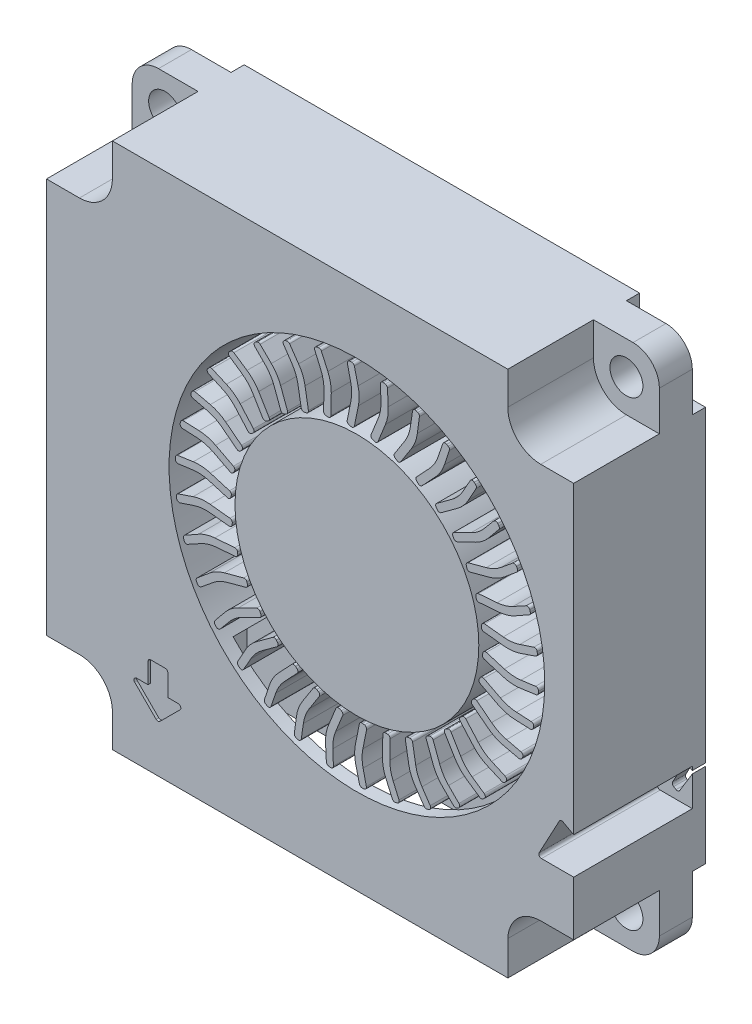
SolidWorks part; units mm, degrees
material "ABS"
ref_plane "Спереди" through (0, 0, 0) normal (0, 0, 1) x (1, 0, 0)
ref_plane "Сверху" through (0, 0, 0) normal (0, 1, 0) x (1, 0, 0)
ref_plane "Справа" through (0, 0, 0) normal (1, 0, 0) x (0, 0, -1)
sketch "Эскиз1" plane through (0, 0, 0) normal (0, 0, 1) x (1, 0, 0)
  line L1 (2, 0) -> (38, 0)
  line L2 (0, 2) -> (0, 38)
  line L3 (2, 40) -> (38, 40)
  line L4 (40, 2) -> (40, 38)
  arc A0 (0, 2) -> (2, 0) centre (2, 2) ccw
  arc A1 (40, 2) -> (38, 0) centre (38, 2) cw
  arc A2 (40, 38) -> (38, 40) centre (38, 38) ccw
  arc A3 (0, 38) -> (2, 40) centre (2, 38) cw
  circle A4 centre (2.5, 37.5) radius 1.25
  circle A5 centre (37.5, 37.5) radius 1.25
  circle A6 centre (37.5, 2.5) radius 1.25
  circle A7 centre (2.5, 2.5) radius 1.25
  point P7 (0, 0)
  point P10 (40, 0)
  point P13 (40, 40)
  point P16 (0, 40)
  dimension "D3" = 2
  dimension "D4" = 2
  dimension "D6" = 2.5
  dimension "D1" = 40
  dimension "D2" = 40
  dimension "D7" = 2.5
  dimension "D5" = 2
extrude "Бобышка-Вытянуть1" add sketch "Эскиз1" along normal blind 10
sketch "Эскиз2" plane through (0, 0, 10) normal (0, 0, 1) x (1, 0, 0)
  line L0 (5, 37.5) -> (5, 40)
  line L1 (5, 40) -> (-1.1472, 40)
  line L2 (-1.1472, 40) -> (-1.1472, 35)
  line L3 (-1.1472, 35) -> (2.5, 35)
  line L4 (37.5, 35) -> (44.7203, 35)
  line L5 (44.7203, 35) -> (44.7203, 44.1762)
  line L6 (44.7203, 44.1762) -> (35, 44.1762)
  line L7 (35, 44.1762) -> (35, 37.5)
  line L8 (37.5, 5.0016) -> (44.7203, 5.0016)
  line L9 (44.7203, 5.0016) -> (44.7203, -1.7129)
  line L10 (44.7203, -1.7129) -> (35.0111, -1.7129)
  line L11 (35.0111, -1.7129) -> (35, 2.5894)
  line L12 (5, 2.5) -> (5, -3.0182)
  line L13 (5, -3.0182) -> (-5.3068, -3.0182)
  line L14 (-5.3068, -3.0182) -> (-5.3068, 5)
  line L15 (-5.3068, 5) -> (2.5, 5)
  arc A0 (2.5, 35) -> (5, 37.5) centre (2.5, 37.5) ccw
  arc A1 (35, 37.5) -> (37.5, 35) centre (37.5, 37.5) ccw
  arc A2 (37.5, 5.0016) -> (35, 2.5894) centre (37.5, 2.5) ccw
  arc A3 (5, 2.5) -> (2.5, 5) centre (2.5, 2.5) ccw
extrude "Вырез-Вытянуть1" cut sketch "Эскиз2" against normal blind 6.5
sketch "Эскиз4" plane through (0, 0, 10) normal (0, 0, 1) x (1, 0, 0)
  line L0 (2, 0) -> (5, 0) construction
  line L1 (5, 0) -> (5, 2.5) construction
  line L2 (2.5, 5) -> (0, 5) construction
  line L3 (0, 5) -> (0, 2) construction
  line L4 (35.0067, 0) -> (38, 0) construction
  line L5 (40, 2) -> (40, 5.0016) construction
  line L6 (40, 5.0016) -> (37.5, 5.0016) construction
  line L7 (35, 2.5894) -> (35.0067, 0) construction
  line L8 (40, 35) -> (40, 38) construction
  line L9 (38, 40) -> (35, 40) construction
  line L10 (35, 40) -> (35, 37.5) construction
  line L11 (37.5, 35) -> (40, 35) construction
  line L12 (0, 38) -> (0, 35) construction
  line L13 (0, 35) -> (2.5, 35) construction
  line L14 (5, 37.5) -> (5, 40) construction
  line L15 (5, 40) -> (2, 40) construction
  line L16 (2, 0) -> (5, 0)
  line L17 (5, 0) -> (5, 2.5)
  line L18 (2.5, 5) -> (0, 5)
  line L19 (0, 5) -> (0, 2)
  line L20 (35.0067, 0) -> (38, 0)
  line L21 (40, 2) -> (40, 5.0016)
  line L22 (40, 5.0016) -> (37.5, 5.0016)
  line L23 (35, 2.5894) -> (35.0067, 0)
  line L24 (40, 35) -> (40, 38)
  line L25 (38, 40) -> (35, 40)
  line L26 (35, 40) -> (35, 37.5)
  line L27 (37.5, 35) -> (40, 35)
  line L28 (0, 38) -> (0, 35)
  line L29 (0, 35) -> (2.5, 35)
  line L30 (5, 37.5) -> (5, 40)
  line L31 (5, 40) -> (2, 40)
  arc A0 (5, 2.5) -> (2.5, 5) centre (2.5, 2.5) ccw construction
  arc A1 (0, 2) -> (2, 0) centre (2, 2) ccw construction
  arc A2 (38, 0) -> (40, 2) centre (38, 2) ccw construction
  arc A3 (37.5, 5.0016) -> (35, 2.5894) centre (37.5, 2.5) ccw construction
  arc A4 (40, 38) -> (38, 40) centre (38, 38) ccw construction
  arc A5 (35, 37.5) -> (37.5, 35) centre (37.5, 37.5) ccw construction
  arc A6 (2, 40) -> (0, 38) centre (2, 38) ccw construction
  arc A7 (2.5, 35) -> (5, 37.5) centre (2.5, 37.5) ccw construction
  arc A8 (5, 2.5) -> (2.5, 5) centre (2.5, 2.5) ccw
  arc A9 (0, 2) -> (2, 0) centre (2, 2) ccw
  arc A10 (38, 0) -> (40, 2) centre (38, 2) ccw
  arc A11 (37.5, 5.0016) -> (35, 2.5894) centre (37.5, 2.5) ccw
  arc A12 (40, 38) -> (38, 40) centre (38, 38) ccw
  arc A13 (35, 37.5) -> (37.5, 35) centre (37.5, 37.5) ccw
  arc A14 (2, 40) -> (0, 38) centre (2, 38) ccw
  arc A15 (2.5, 35) -> (5, 37.5) centre (2.5, 37.5) ccw
extrude "Вырез-Вытянуть2" cut sketch "Эскиз4" against normal blind 6.5 from offset 9 offset against normal yes
sketch "Эскиз5" plane through (0, 0, 0) normal (0, -1, 0) x (1, 0, 0)
  line L0 (5, 10) -> (35.0067, 10) construction
  line L1 (6.2, 9) -> (33.8067, 9)
  line L2 (6.2, 9) -> (6.2, 1)
  line L3 (6.2, 1) -> (33.8067, 1)
  line L4 (33.8067, 9) -> (33.8067, 1)
  line L5 (35.0067, 3.5) -> (35.0067, 10) construction
  line L6 (5, 10) -> (5, 3.5) construction
  line L7 (5, 0) -> (35.0067, 0) construction
  dimension "D1" = 1
  dimension "D2" = 1.2
  dimension "D3" = 1.2
  dimension "D4" = 1
extrude "Вырез-Вытянуть3" cut sketch "Эскиз5" against normal blind 11
sketch "Эскиз6" plane through (0, 0, 10) normal (0, 0, 1) x (1, 0, 0)
  line L0 (40, 5.0016) -> (40, 35) construction
  line L1 (5, 0) -> (35.0067, 0) construction
  circle A0 centre (23.55, 20.75) radius 14.25
  circle A1 centre (23.55, 20.75) radius 9.25
  dimension "D1" = 16.45
  dimension "D2" = 20.75
  dimension "D3" = 5
extrude "Вырез-Вытянуть4" cut sketch "Эскиз6" against normal blind 8
sketch "Эскиз8" plane through (0, 0, 2) normal (0, 0, 1) x (1, 0, 0)
  line L0 (23.0257, 34.5383) -> (23.1635, 34.5383)
  line L1 (23.3579, 34.3851) -> (23.6377, 33.2218)
  line L2 (23.6614, 31.9259) -> (23.3607, 30.4382)
  line L3 (23.125, 30.2818) -> (22.9708, 30.3129)
  line L4 (22.8144, 30.5486) -> (23.0961, 31.9425)
  line L5 (23.0798, 33.2069) -> (22.8308, 34.2936)
  line L6 (25.5683, 34.3999) -> (25.7036, 34.3746)
  line L7 (25.8666, 34.1882) -> (25.9279, 32.9933)
  line L8 (25.7131, 31.7152) -> (25.1441, 30.308)
  line L9 (24.8837, 30.1976) -> (24.7378, 30.2565)
  line L10 (24.6274, 30.5169) -> (25.1605, 31.8354)
  line L11 (25.3768, 33.0812) -> (25.3317, 34.1952)
  line L12 (28.0421, 33.7966) -> (28.1705, 33.7469)
  line L13 (28.2965, 33.5337) -> (28.1371, 32.3479)
  line L14 (27.6911, 31.131) -> (26.8732, 29.8523)
  line L15 (26.597, 29.7916) -> (26.4644, 29.8764)
  line L16 (26.4037, 30.1527) -> (27.17, 31.3507)
  line L17 (27.6115, 32.5356) -> (27.7719, 33.6389)
  line L18 (30.3629, 32.749) -> (30.48, 32.6765)
  line L19 (30.5646, 32.4439) -> (30.1901, 31.3076)
  line L20 (29.5281, 30.1933) -> (28.4892, 29.0867)
  line L21 (28.2065, 29.0778) -> (28.0918, 29.1855)
  line L22 (28.0828, 29.4682) -> (29.0562, 30.505)
  line L23 (29.7079, 31.5886) -> (30.0683, 32.6437)
  line L24 (32.4517, 31.2929) -> (32.5535, 31.2001)
  line L25 (32.5939, 30.9559) -> (32.017, 29.9077)
  line L26 (31.1615, 28.934) -> (29.937, 28.0372)
  line L27 (29.6575, 28.0804) -> (29.5645, 28.2073)
  line L28 (29.6076, 28.4869) -> (30.7549, 29.3272)
  line L29 (31.5947, 30.2725) -> (32.1428, 31.2434)
  line L30 (34.2374, 29.4777) -> (34.3204, 29.3678)
  line L31 (34.3153, 29.1203) -> (33.5556, 28.1959)
  line L32 (32.5357, 27.3961) -> (31.1672, 26.7395)
  line L33 (30.9004, 26.8333) -> (30.8323, 26.9752)
  line L34 (30.9261, 27.242) -> (32.2083, 27.8572)
  line L35 (33.2075, 28.6322) -> (33.9246, 29.4858)
  line L36 (35.6591, 27.3653) -> (35.7205, 27.242)
  line L37 (35.67, 26.9996) -> (34.7534, 26.2306)
  line L38 (33.6039, 25.6318) -> (32.1381, 25.2379)
  line L39 (31.8931, 25.3791) -> (31.8522, 25.5311)
  line L40 (31.9934, 25.7761) -> (33.3668, 26.1452)
  line L41 (34.4914, 26.7234) -> (35.3532, 27.4307)
  line L42 (36.6685, 25.0276) -> (36.7062, 24.8951)
  line L43 (36.612, 24.6662) -> (35.5697, 24.0787)
  line L44 (34.3298, 23.7013) -> (32.8165, 23.5834)
  line L45 (32.6016, 23.7672) -> (32.5894, 23.9241)
  line L46 (32.7732, 24.1391) -> (34.191, 24.2495)
  line L47 (35.4027, 24.6112) -> (36.3798, 25.1481)
  line L48 (37.2311, 22.5442) -> (37.2438, 22.4071)
  line L49 (37.1092, 22.1993) -> (35.9767, 21.8134)
  line L50 (34.6885, 21.6703) -> (33.1794, 21.8324)
  line L51 (33.0019, 22.0526) -> (33.0187, 22.2091)
  line L52 (33.2389, 22.3866) -> (34.6529, 22.2347)
  line L53 (35.9104, 22.3676) -> (36.9695, 22.7158)
  line L54 (37.3279, 19.9998) -> (37.3152, 19.8627)
  line L55 (37.1446, 19.6832) -> (35.9605, 19.5119)
  line L56 (34.668, 19.6079) -> (33.2143, 20.0446)
  line L57 (33.0803, 20.2937) -> (33.1256, 20.4444)
  line L58 (33.3747, 20.5784) -> (34.7367, 20.1692)
  line L59 (35.9972, 20.0688) -> (37.1022, 20.2165)
  line L60 (36.9554, 17.4809) -> (36.9177, 17.3484)
  line L61 (36.7171, 17.2033) -> (35.5217, 17.2526)
  line L62 (34.2688, 17.5844) -> (32.9201, 18.2808)
  line L63 (32.8342, 18.5503) -> (32.9064, 18.6901)
  line L64 (33.1759, 18.776) -> (34.4395, 18.1236)
  line L65 (35.6601, 17.7933) -> (36.7734, 17.7354)
  line L66 (36.1265, 15.0733) -> (36.0651, 14.95)
  line L67 (35.8412, 14.8443) -> (34.6752, 15.1123)
  line L68 (33.5046, 15.6687) -> (32.3069, 16.6011)
  line L69 (32.2719, 16.8817) -> (32.3686, 17.0059)
  line L70 (32.6493, 17.0409) -> (33.7715, 16.1674)
  line L71 (34.9106, 15.6184) -> (35.9944, 15.3569)
  line L72 (34.8692, 12.859) -> (34.7863, 12.7491)
  line L73 (34.5468, 12.6863) -> (33.4499, 13.1641)
  line L74 (32.4014, 13.9261) -> (31.3954, 15.0626)
  line L75 (31.4126, 15.345) -> (31.5305, 15.4493)
  line L76 (31.8128, 15.4321) -> (32.7554, 14.3672)
  line L77 (33.7742, 13.6183) -> (34.7915, 13.1621)
  line L78 (33.2266, 10.9135) -> (33.1248, 10.8207)
  line L79 (32.8778, 10.803) -> (31.8874, 11.4741)
  line L80 (30.9968, 12.4158) -> (30.2168, 13.7179)
  line L81 (30.2856, 13.9922) -> (30.4206, 14.0731)
  line L82 (30.6949, 14.0043) -> (31.4258, 12.7844)
  line L83 (32.2897, 11.861) -> (33.2058, 11.2256)
  line L84 (31.2543, 9.3029) -> (31.1372, 9.2304)
  line L85 (30.8913, 9.2583) -> (30.041, 10.1001)
  line L86 (29.3386, 11.1894) -> (28.8111, 12.6126)
  line L87 (28.9291, 12.8696) -> (29.0767, 12.9243)
  line L88 (29.3338, 12.8063) -> (29.828, 11.4729)
  line L89 (30.5075, 10.4065) -> (31.2913, 9.6136)
  line L90 (29.0198, 8.0822) -> (28.8913, 8.0324)
  line L91 (28.6547, 8.105) -> (27.9736, 9.0887)
  line L92 (27.4833, 10.2885) -> (27.2263, 11.7844)
  line L93 (27.3895, 12.0154) -> (27.5446, 12.0421)
  line L94 (27.7756, 11.8788) -> (28.0164, 10.4772)
  line L95 (28.4884, 9.3041) -> (29.1132, 8.3807)
  line L96 (26.5989, 7.2928) -> (26.4635, 7.2675)
  line L97 (26.2442, 7.3824) -> (25.7555, 8.4744)
  line L98 (25.4941, 9.7439) -> (25.5163, 11.2616)
  line L99 (25.7192, 11.4586) -> (25.8766, 11.4563)
  line L100 (26.0736, 11.2534) -> (26.0528, 9.8315)
  line L101 (26.3011, 8.5916) -> (26.7456, 7.5691)
  line L102 (24.0743, 6.9617) -> (23.9365, 6.9617)
  line L103 (23.7421, 7.1149) -> (23.4623, 8.2782)
  line L104 (23.4386, 9.5741) -> (23.7393, 11.0618)
  line L105 (23.975, 11.2182) -> (24.1292, 11.1871)
  line L106 (24.2856, 10.9514) -> (24.0039, 9.5575)
  line L107 (24.0202, 8.2931) -> (24.2692, 7.2064)
  line L108 (21.5317, 7.1001) -> (21.3964, 7.1254)
  line L109 (21.2334, 7.3118) -> (21.1721, 8.5067)
  line L110 (21.3869, 9.7848) -> (21.9559, 11.192)
  line L111 (22.2163, 11.3024) -> (22.3622, 11.2435)
  line L112 (22.4726, 10.9831) -> (21.9395, 9.6646)
  line L113 (21.7232, 8.4188) -> (21.7683, 7.3048)
  line L114 (19.0579, 7.7034) -> (18.9295, 7.7531)
  line L115 (18.8035, 7.9663) -> (18.9629, 9.1521)
  line L116 (19.4089, 10.369) -> (20.2268, 11.6477)
  line L117 (20.503, 11.7084) -> (20.6356, 11.6236)
  line L118 (20.6963, 11.3473) -> (19.93, 10.1493)
  line L119 (19.4885, 8.9644) -> (19.3281, 7.8611)
  line L120 (16.7371, 8.751) -> (16.62, 8.8235)
  line L121 (16.5354, 9.0561) -> (16.9099, 10.1924)
  line L122 (17.5719, 11.3067) -> (18.6108, 12.4133)
  line L123 (18.8935, 12.4222) -> (19.0082, 12.3145)
  line L124 (19.0172, 12.0318) -> (18.0438, 10.995)
  line L125 (17.3921, 9.9114) -> (17.0317, 8.8563)
  line L126 (14.6483, 10.2071) -> (14.5465, 10.2999)
  line L127 (14.5061, 10.5441) -> (15.083, 11.5923)
  line L128 (15.9385, 12.566) -> (17.163, 13.4628)
  line L129 (17.4425, 13.4196) -> (17.5355, 13.2927)
  line L130 (17.4924, 13.0131) -> (16.3451, 12.1728)
  line L131 (15.5053, 11.2275) -> (14.9572, 10.2566)
  line L132 (12.8626, 12.0223) -> (12.7796, 12.1322)
  line L133 (12.7847, 12.3797) -> (13.5444, 13.3041)
  line L134 (14.5643, 14.1039) -> (15.9328, 14.7605)
  line L135 (16.1996, 14.6667) -> (16.2677, 14.5248)
  line L136 (16.1739, 14.258) -> (14.8917, 13.6428)
  line L137 (13.8925, 12.8678) -> (13.1754, 12.0142)
  line L138 (11.4409, 14.1347) -> (11.3795, 14.258)
  line L139 (11.43, 14.5004) -> (12.3466, 15.2694)
  line L140 (13.4961, 15.8682) -> (14.9619, 16.2621)
  line L141 (15.2069, 16.1209) -> (15.2478, 15.9689)
  line L142 (15.1066, 15.7239) -> (13.7332, 15.3548)
  line L143 (12.6086, 14.7766) -> (11.7468, 14.0693)
  line L144 (10.4315, 16.4724) -> (10.3938, 16.6049)
  line L145 (10.488, 16.8338) -> (11.5303, 17.4213)
  line L146 (12.7702, 17.7987) -> (14.2835, 17.9166)
  line L147 (14.4984, 17.7328) -> (14.5106, 17.5759)
  line L148 (14.3268, 17.3609) -> (12.909, 17.2505)
  line L149 (11.6973, 16.8888) -> (10.7202, 16.3519)
  line L150 (9.8689, 18.9558) -> (9.8562, 19.0929)
  line L151 (9.9908, 19.3007) -> (11.1233, 19.6866)
  line L152 (12.4115, 19.8297) -> (13.9206, 19.6676)
  line L153 (14.0981, 19.4474) -> (14.0813, 19.2909)
  line L154 (13.8611, 19.1134) -> (12.4471, 19.2653)
  line L155 (11.1896, 19.1324) -> (10.1305, 18.7842)
  line L156 (9.7721, 21.5002) -> (9.7848, 21.6373)
  line L157 (9.9554, 21.8168) -> (11.1395, 21.9881)
  line L158 (12.432, 21.8921) -> (13.8857, 21.4554)
  line L159 (14.0197, 21.2063) -> (13.9744, 21.0556)
  line L160 (13.7253, 20.9216) -> (12.3633, 21.3308)
  line L161 (11.1028, 21.4312) -> (9.9978, 21.2835)
  line L162 (10.1446, 24.0191) -> (10.1823, 24.1516)
  line L163 (10.3829, 24.2967) -> (11.5783, 24.2474)
  line L164 (12.8312, 23.9156) -> (14.1799, 23.2192)
  line L165 (14.2658, 22.9497) -> (14.1936, 22.8099)
  line L166 (13.9241, 22.724) -> (12.6605, 23.3764)
  line L167 (11.4399, 23.7067) -> (10.3266, 23.7646)
  line L168 (10.9735, 26.4267) -> (11.0349, 26.55)
  line L169 (11.2588, 26.6557) -> (12.4248, 26.3877)
  line L170 (13.5954, 25.8313) -> (14.7931, 24.8989)
  line L171 (14.8281, 24.6183) -> (14.7314, 24.4941)
  line L172 (14.4507, 24.4591) -> (13.3285, 25.3326)
  line L173 (12.1894, 25.8816) -> (11.1056, 26.1431)
  line L174 (12.2308, 28.641) -> (12.3137, 28.7509)
  line L175 (12.5532, 28.8137) -> (13.6501, 28.3359)
  line L176 (14.6986, 27.5739) -> (15.7046, 26.4374)
  line L177 (15.6874, 26.155) -> (15.5695, 26.0507)
  line L178 (15.2872, 26.0679) -> (14.3446, 27.1328)
  line L179 (13.3258, 27.8817) -> (12.3085, 28.3379)
  line L180 (13.8734, 30.5865) -> (13.9752, 30.6793)
  line L181 (14.2222, 30.697) -> (15.2126, 30.0259)
  line L182 (16.1032, 29.0842) -> (16.8832, 27.7821)
  line L183 (16.8144, 27.5078) -> (16.6794, 27.4269)
  line L184 (16.4051, 27.4957) -> (15.6742, 28.7156)
  line L185 (14.8103, 29.639) -> (13.8942, 30.2744)
  line L186 (15.8457, 32.1971) -> (15.9628, 32.2696)
  line L187 (16.2087, 32.2417) -> (17.059, 31.3999)
  line L188 (17.7614, 30.3106) -> (18.2889, 28.8874)
  line L189 (18.1709, 28.6304) -> (18.0233, 28.5757)
  line L190 (17.7662, 28.6937) -> (17.272, 30.0271)
  line L191 (16.5925, 31.0935) -> (15.8087, 31.8864)
  line L192 (18.0802, 33.4178) -> (18.2087, 33.4676)
  line L193 (18.4453, 33.395) -> (19.1264, 32.4113)
  line L194 (19.6167, 31.2115) -> (19.8737, 29.7156)
  line L195 (19.7105, 29.4846) -> (19.5554, 29.4579)
  line L196 (19.3244, 29.6212) -> (19.0836, 31.0228)
  line L197 (18.6116, 32.1959) -> (17.9868, 33.1193)
  line L198 (20.5011, 34.2072) -> (20.6365, 34.2325)
  line L199 (20.8558, 34.1176) -> (21.3445, 33.0256)
  line L200 (21.6059, 31.7561) -> (21.5837, 30.2384)
  line L201 (21.3808, 30.0414) -> (21.2234, 30.0437)
  line L202 (21.0264, 30.2466) -> (21.0472, 31.6685)
  line L203 (20.7989, 32.9084) -> (20.3544, 33.9309)
  arc A0 (23.6377, 33.2218) -> (23.6614, 31.9259) centre (20.7209, 32.5203) cw
  arc A1 (23.0798, 33.2069) -> (23.0961, 31.9425) centre (20.1556, 32.5369) cw
  arc A2 (23.0257, 34.5383) -> (22.8308, 34.2936) centre (23.0257, 34.3383) ccw
  arc A3 (23.3579, 34.3851) -> (23.1635, 34.5383) centre (23.1635, 34.3383) ccw
  arc A4 (22.9708, 30.3129) -> (22.8144, 30.5486) centre (23.0104, 30.509) cw
  arc A5 (23.3607, 30.4382) -> (23.125, 30.2818) centre (23.1647, 30.4778) cw
  arc A6 (25.9279, 32.9933) -> (25.7131, 31.7152) centre (22.9318, 32.8397) cw
  arc A7 (25.3768, 33.0812) -> (25.1605, 31.8354) centre (22.3792, 32.9599) cw
  arc A8 (25.5683, 34.3999) -> (25.3317, 34.1952) centre (25.5315, 34.2033) ccw
  arc A9 (25.8666, 34.1882) -> (25.7036, 34.3746) centre (25.6669, 34.178) ccw
  arc A10 (24.7378, 30.2565) -> (24.6274, 30.5169) centre (24.8128, 30.442) cw
  arc A11 (25.1441, 30.308) -> (24.8837, 30.1976) centre (24.9587, 30.383) cw
  arc A12 (28.1371, 32.3479) -> (27.6911, 31.131) centre (25.1638, 32.7475) cw
  arc A13 (27.6115, 32.5356) -> (27.17, 31.3507) centre (24.6427, 32.9672) cw
  arc A14 (28.0421, 33.7966) -> (27.7719, 33.6389) centre (27.9698, 33.6101) ccw
  arc A15 (28.2965, 33.5337) -> (28.1705, 33.7469) centre (28.0982, 33.5604) ccw
  arc A16 (26.4644, 29.8764) -> (26.4037, 30.1527) centre (26.5722, 30.0449) cw
  arc A17 (26.8732, 29.8523) -> (26.597, 29.7916) centre (26.7048, 29.9601) cw
  arc A18 (30.1901, 31.3076) -> (29.5281, 30.1933) centre (27.3409, 32.2466) cw
  arc A19 (29.7079, 31.5886) -> (29.0562, 30.505) centre (26.869, 32.5583) cw
  arc A20 (30.3629, 32.749) -> (30.0683, 32.6437) centre (30.2576, 32.579) ccw
  arc A21 (30.5646, 32.4439) -> (30.48, 32.6765) centre (30.3747, 32.5065) ccw
  arc A22 (28.0918, 29.1855) -> (28.0828, 29.4682) centre (28.2287, 29.3313) cw
  arc A23 (28.4892, 29.0867) -> (28.2065, 29.0778) centre (28.3434, 29.2236) cw
  arc A24 (32.017, 29.9077) -> (31.1615, 28.934) centre (29.3888, 31.3543) cw
  arc A25 (31.5947, 30.2725) -> (30.7549, 29.3272) centre (28.9823, 31.7474) cw
  arc A26 (32.4517, 31.2929) -> (32.1428, 31.2434) centre (32.317, 31.1451) ccw
  arc A27 (32.5939, 30.9559) -> (32.5535, 31.2001) centre (32.4187, 31.0523) ccw
  arc A28 (29.5645, 28.2073) -> (29.6076, 28.4869) centre (29.7258, 28.3255) cw
  arc A29 (29.937, 28.0372) -> (29.6575, 28.0804) centre (29.8188, 28.1985) cw
  arc A30 (33.5556, 28.1959) -> (32.5357, 27.3961) centre (31.238, 30.1009) cw
  arc A31 (33.2075, 28.6322) -> (32.2083, 27.8572) centre (30.9105, 30.562) cw
  arc A32 (34.2374, 29.4777) -> (33.9246, 29.4858) centre (34.0778, 29.3572) ccw
  arc A33 (34.3153, 29.1203) -> (34.3204, 29.3678) centre (34.1608, 29.2472) ccw
  arc A34 (30.8323, 26.9752) -> (30.9261, 27.242) centre (31.0126, 27.0617) cw
  arc A35 (31.1672, 26.7395) -> (30.9004, 26.8333) centre (31.0807, 26.9198) cw
  arc A36 (34.7534, 26.2306) -> (33.6039, 25.6318) centre (32.8253, 28.529) cw
  arc A37 (34.4914, 26.7234) -> (33.3668, 26.1452) centre (32.5882, 29.0424) cw
  arc A38 (35.6591, 27.3653) -> (35.3532, 27.4307) centre (35.4801, 27.2761) ccw
  arc A39 (35.67, 26.9996) -> (35.7205, 27.242) centre (35.5415, 27.1528) ccw
  arc A40 (31.8522, 25.5311) -> (31.9934, 25.7761) centre (32.0454, 25.583) cw
  arc A41 (32.1381, 25.2379) -> (31.8931, 25.3791) centre (32.0862, 25.431) cw
  arc A42 (35.5697, 24.0787) -> (34.3298, 23.7013) centre (34.0967, 26.6922) cw
  arc A43 (35.4027, 24.6112) -> (34.191, 24.2495) centre (33.958, 27.2405) cw
  arc A44 (36.6685, 25.0276) -> (36.3798, 25.1481) centre (36.4761, 24.9729) ccw
  arc A45 (36.612, 24.6662) -> (36.7062, 24.8951) centre (36.5138, 24.8404) ccw
  arc A46 (32.5894, 23.9241) -> (32.7732, 24.1391) centre (32.7888, 23.9397) cw
  arc A47 (32.8165, 23.5834) -> (32.6016, 23.7672) centre (32.801, 23.7828) cw
  arc A48 (35.9767, 21.8134) -> (34.6885, 21.6703) centre (35.009, 24.6531) cw
  arc A49 (35.9104, 22.3676) -> (34.6529, 22.2347) centre (34.9734, 25.2175) cw
  arc A50 (37.2311, 22.5442) -> (36.9695, 22.7158) centre (37.032, 22.5258) ccw
  arc A51 (37.1092, 22.1993) -> (37.2438, 22.4071) centre (37.0447, 22.3887) ccw
  arc A52 (33.0187, 22.2091) -> (33.2389, 22.3866) centre (33.2176, 22.1877) cw
  arc A53 (33.1794, 21.8324) -> (33.0019, 22.0526) centre (33.2007, 22.0313) cw
  arc A54 (35.9605, 19.5119) -> (34.668, 19.6079) centre (35.5311, 22.481) cw
  arc A55 (35.9972, 20.0688) -> (34.7367, 20.1692) centre (35.5998, 23.0424) cw
  arc A56 (37.3279, 19.9998) -> (37.1022, 20.2165) centre (37.1287, 20.0182) ccw
  arc A57 (37.1446, 19.6832) -> (37.3152, 19.8627) centre (37.116, 19.8811) ccw
  arc A58 (33.1256, 20.4444) -> (33.3747, 20.5784) centre (33.3171, 20.3869) cw
  arc A59 (33.2143, 20.0446) -> (33.0803, 20.2937) centre (33.2719, 20.2361) cw
  arc A60 (35.5217, 17.2526) -> (34.2688, 17.5844) centre (35.6452, 20.25) cw
  arc A61 (35.6601, 17.7933) -> (34.4395, 18.1236) centre (35.8159, 20.7892) cw
  arc A62 (36.9554, 17.4809) -> (36.7734, 17.7354) centre (36.7631, 17.5356) ccw
  arc A63 (36.7171, 17.2033) -> (36.9177, 17.3484) centre (36.7254, 17.4032) ccw
  arc A64 (32.9064, 18.6901) -> (33.1759, 18.776) centre (33.0841, 18.5983) cw
  arc A65 (32.9201, 18.2808) -> (32.8342, 18.5503) centre (33.0119, 18.4585) cw
  arc A66 (34.6752, 15.1123) -> (33.5046, 15.6687) centre (35.3474, 18.0361) cw
  arc A67 (34.9106, 15.6184) -> (33.7715, 16.1674) centre (35.6142, 18.5347) cw
  arc A68 (36.1265, 15.0733) -> (35.9944, 15.3569) centre (35.9474, 15.1625) ccw
  arc A69 (35.8412, 14.8443) -> (36.0651, 14.95) centre (35.8861, 15.0392) ccw
  arc A70 (32.3686, 17.0059) -> (32.6493, 17.0409) centre (32.5264, 16.8831) cw
  arc A71 (32.3069, 16.6011) -> (32.2719, 16.8817) centre (32.4297, 16.7589) cw
  arc A72 (33.4499, 13.1641) -> (32.4014, 13.9261) centre (34.6478, 15.9145) cw
  arc A73 (33.7742, 13.6183) -> (32.7554, 14.3672) centre (35.0017, 16.3556) cw
  arc A74 (34.8692, 12.859) -> (34.7915, 13.1621) centre (34.7096, 12.9796) ccw
  arc A75 (34.5468, 12.6863) -> (34.7863, 12.7491) centre (34.6266, 12.8697) ccw
  arc A76 (31.5305, 15.4493) -> (31.8128, 15.4321) centre (31.663, 15.2995) cw
  arc A77 (31.3954, 15.0626) -> (31.4126, 15.345) centre (31.5452, 15.1952) cw
  arc A78 (31.8874, 11.4741) -> (30.9968, 12.4158) centre (33.5703, 13.9576) cw
  arc A79 (32.2897, 11.861) -> (31.4258, 12.7844) centre (33.9993, 14.3262) cw
  arc A80 (33.2266, 10.9135) -> (33.2058, 11.2256) centre (33.0918, 11.0613) ccw
  arc A81 (32.8778, 10.803) -> (33.1248, 10.8207) centre (32.99, 10.9685) ccw
  arc A82 (30.4206, 14.0731) -> (30.6949, 14.0043) centre (30.5234, 13.9016) cw
  arc A83 (30.2168, 13.7179) -> (30.2856, 13.9922) centre (30.3883, 13.8207) cw
  arc A84 (30.041, 10.1001) -> (29.3386, 11.1894) centre (32.1516, 12.2321) cw
  arc A85 (30.5075, 10.4065) -> (29.828, 11.4729) centre (32.641, 12.5155) cw
  arc A86 (31.2543, 9.3029) -> (31.2913, 9.6136) centre (31.1491, 9.473) ccw
  arc A87 (30.8913, 9.2583) -> (31.1372, 9.2304) centre (31.032, 9.4005) ccw
  arc A88 (29.0767, 12.9243) -> (29.3338, 12.8063) centre (29.1462, 12.7368) cw
  arc A89 (28.8111, 12.6126) -> (28.9291, 12.8696) centre (28.9986, 12.6821) cw
  arc A90 (27.9736, 9.0887) -> (27.4833, 10.2885) centre (30.44, 10.7965) cw
  arc A91 (28.4884, 9.3041) -> (28.0164, 10.4772) centre (30.9731, 10.9853) cw
  arc A92 (29.0198, 8.0822) -> (29.1132, 8.3807) centre (28.9475, 8.2687) ccw
  arc A93 (28.6547, 8.105) -> (28.8913, 8.0324) centre (28.8191, 8.2189) ccw
  arc A94 (27.5446, 12.0421) -> (27.7756, 11.8788) centre (27.5785, 11.845) cw
  arc A95 (27.2263, 11.7844) -> (27.3895, 12.0154) centre (27.4234, 11.8183) cw
  arc A96 (25.7555, 8.4744) -> (25.4941, 9.7439) centre (28.4937, 9.7) cw
  arc A97 (26.3011, 8.5916) -> (26.0528, 9.8315) centre (29.0525, 9.7875) cw
  arc A98 (26.5989, 7.2928) -> (26.7456, 7.5691) centre (26.5622, 7.4894) ccw
  arc A99 (26.2442, 7.3824) -> (26.4635, 7.2675) centre (26.4268, 7.4641) ccw
  arc A100 (25.8766, 11.4563) -> (26.0736, 11.2534) centre (25.8736, 11.2563) cw
  arc A101 (25.5163, 11.2616) -> (25.7192, 11.4586) centre (25.7163, 11.2586) cw
  arc A102 (23.4623, 8.2782) -> (23.4386, 9.5741) centre (26.3791, 8.9797) cw
  arc A103 (24.0202, 8.2931) -> (24.0039, 9.5575) centre (26.9444, 8.9631) cw
  arc A104 (24.0743, 6.9617) -> (24.2692, 7.2064) centre (24.0743, 7.1617) ccw
  arc A105 (23.7421, 7.1149) -> (23.9365, 6.9617) centre (23.9365, 7.1617) ccw
  arc A106 (24.1292, 11.1871) -> (24.2856, 10.9514) centre (24.0896, 10.991) cw
  arc A107 (23.7393, 11.0618) -> (23.975, 11.2182) centre (23.9353, 11.0222) cw
  arc A108 (21.1721, 8.5067) -> (21.3869, 9.7848) centre (24.1682, 8.6603) cw
  arc A109 (21.7232, 8.4188) -> (21.9395, 9.6646) centre (24.7208, 8.5401) cw
  arc A110 (21.5317, 7.1001) -> (21.7683, 7.3048) centre (21.5685, 7.2967) ccw
  arc A111 (21.2334, 7.3118) -> (21.3964, 7.1254) centre (21.4331, 7.322) ccw
  arc A112 (22.3622, 11.2435) -> (22.4726, 10.9831) centre (22.2872, 11.058) cw
  arc A113 (21.9559, 11.192) -> (22.2163, 11.3024) centre (22.1413, 11.117) cw
  arc A114 (18.9629, 9.1521) -> (19.4089, 10.369) centre (21.9362, 8.7525) cw
  arc A115 (19.4885, 8.9644) -> (19.93, 10.1493) centre (22.4573, 8.5328) cw
  arc A116 (19.0579, 7.7034) -> (19.3281, 7.8611) centre (19.1302, 7.8899) ccw
  arc A117 (18.8035, 7.9663) -> (18.9295, 7.7531) centre (19.0018, 7.9396) ccw
  arc A118 (20.6356, 11.6236) -> (20.6963, 11.3473) centre (20.5278, 11.4551) cw
  arc A119 (20.2268, 11.6477) -> (20.503, 11.7084) centre (20.3952, 11.5399) cw
  arc A120 (16.9099, 10.1924) -> (17.5719, 11.3067) centre (19.7591, 9.2534) cw
  arc A121 (17.3921, 9.9114) -> (18.0438, 10.995) centre (20.231, 8.9417) cw
  arc A122 (16.7371, 8.751) -> (17.0317, 8.8563) centre (16.8424, 8.921) ccw
  arc A123 (16.5354, 9.0561) -> (16.62, 8.8235) centre (16.7253, 8.9935) ccw
  arc A124 (19.0082, 12.3145) -> (19.0172, 12.0318) centre (18.8713, 12.1687) cw
  arc A125 (18.6108, 12.4133) -> (18.8935, 12.4222) centre (18.7566, 12.2764) cw
  arc A126 (15.083, 11.5923) -> (15.9385, 12.566) centre (17.7112, 10.1457) cw
  arc A127 (15.5053, 11.2275) -> (16.3451, 12.1728) centre (18.1177, 9.7526) cw
  arc A128 (14.6483, 10.2071) -> (14.9572, 10.2566) centre (14.783, 10.3549) ccw
  arc A129 (14.5061, 10.5441) -> (14.5465, 10.2999) centre (14.6813, 10.4477) ccw
  arc A130 (17.5355, 13.2927) -> (17.4924, 13.0131) centre (17.3742, 13.1745) cw
  arc A131 (17.163, 13.4628) -> (17.4425, 13.4196) centre (17.2812, 13.3015) cw
  arc A132 (13.5444, 13.3041) -> (14.5643, 14.1039) centre (15.862, 11.3991) cw
  arc A133 (13.8925, 12.8678) -> (14.8917, 13.6428) centre (16.1895, 10.938) cw
  arc A134 (12.8626, 12.0223) -> (13.1754, 12.0142) centre (13.0222, 12.1428) ccw
  arc A135 (12.7847, 12.3797) -> (12.7796, 12.1322) centre (12.9392, 12.2528) ccw
  arc A136 (16.2677, 14.5248) -> (16.1739, 14.258) centre (16.0874, 14.4383) cw
  arc A137 (15.9328, 14.7605) -> (16.1996, 14.6667) centre (16.0193, 14.5802) cw
  arc A138 (12.3466, 15.2694) -> (13.4961, 15.8682) centre (14.2747, 12.971) cw
  arc A139 (12.6086, 14.7766) -> (13.7332, 15.3548) centre (14.5118, 12.4576) cw
  arc A140 (11.4409, 14.1347) -> (11.7468, 14.0693) centre (11.6199, 14.2239) ccw
  arc A141 (11.43, 14.5004) -> (11.3795, 14.258) centre (11.5585, 14.3472) ccw
  arc A142 (15.2478, 15.9689) -> (15.1066, 15.7239) centre (15.0546, 15.917) cw
  arc A143 (14.9619, 16.2621) -> (15.2069, 16.1209) centre (15.0138, 16.069) cw
  arc A144 (11.5303, 17.4213) -> (12.7702, 17.7987) centre (13.0033, 14.8078) cw
  arc A145 (11.6973, 16.8888) -> (12.909, 17.2505) centre (13.142, 14.2595) cw
  arc A146 (10.4315, 16.4724) -> (10.7202, 16.3519) centre (10.6239, 16.5271) ccw
  arc A147 (10.488, 16.8338) -> (10.3938, 16.6049) centre (10.5862, 16.6596) ccw
  arc A148 (14.5106, 17.5759) -> (14.3268, 17.3609) centre (14.3112, 17.5603) cw
  arc A149 (14.2835, 17.9166) -> (14.4984, 17.7328) centre (14.299, 17.7172) cw
  arc A150 (11.1233, 19.6866) -> (12.4115, 19.8297) centre (12.091, 16.8469) cw
  arc A151 (11.1896, 19.1324) -> (12.4471, 19.2653) centre (12.1266, 16.2825) cw
  arc A152 (9.8689, 18.9558) -> (10.1305, 18.7842) centre (10.068, 18.9742) ccw
  arc A153 (9.9908, 19.3007) -> (9.8562, 19.0929) centre (10.0553, 19.1113) ccw
  arc A154 (14.0813, 19.2909) -> (13.8611, 19.1134) centre (13.8824, 19.3123) cw
  arc A155 (13.9206, 19.6676) -> (14.0981, 19.4474) centre (13.8993, 19.4687) cw
  arc A156 (11.1395, 21.9881) -> (12.432, 21.8921) centre (11.5689, 19.019) cw
  arc A157 (11.1028, 21.4312) -> (12.3633, 21.3308) centre (11.5002, 18.4576) cw
  arc A158 (9.7721, 21.5002) -> (9.9978, 21.2835) centre (9.9713, 21.4818) ccw
  arc A159 (9.9554, 21.8168) -> (9.7848, 21.6373) centre (9.984, 21.6189) ccw
  arc A160 (13.9744, 21.0556) -> (13.7253, 20.9216) centre (13.7829, 21.1131) cw
  arc A161 (13.8857, 21.4554) -> (14.0197, 21.2063) centre (13.8281, 21.2639) cw
  arc A162 (11.5783, 24.2474) -> (12.8312, 23.9156) centre (11.4548, 21.25) cw
  arc A163 (11.4399, 23.7067) -> (12.6605, 23.3764) centre (11.2841, 20.7108) cw
  arc A164 (10.1446, 24.0191) -> (10.3266, 23.7646) centre (10.3369, 23.9644) ccw
  arc A165 (10.3829, 24.2967) -> (10.1823, 24.1516) centre (10.3746, 24.0968) ccw
  arc A166 (14.1936, 22.8099) -> (13.9241, 22.724) centre (14.0159, 22.9017) cw
  arc A167 (14.1799, 23.2192) -> (14.2658, 22.9497) centre (14.0881, 23.0415) cw
  arc A168 (12.4248, 26.3877) -> (13.5954, 25.8313) centre (11.7526, 23.4639) cw
  arc A169 (12.1894, 25.8816) -> (13.3285, 25.3326) centre (11.4858, 22.9653) cw
  arc A170 (10.9735, 26.4267) -> (11.1056, 26.1431) centre (11.1526, 26.3375) ccw
  arc A171 (11.2588, 26.6557) -> (11.0349, 26.55) centre (11.2139, 26.4608) ccw
  arc A172 (14.7314, 24.4941) -> (14.4507, 24.4591) centre (14.5736, 24.6169) cw
  arc A173 (14.7931, 24.8989) -> (14.8281, 24.6183) centre (14.6703, 24.7411) cw
  arc A174 (13.6501, 28.3359) -> (14.6986, 27.5739) centre (12.4522, 25.5855) cw
  arc A175 (13.3258, 27.8817) -> (14.3446, 27.1328) centre (12.0983, 25.1444) cw
  arc A176 (12.2308, 28.641) -> (12.3085, 28.3379) centre (12.3904, 28.5204) ccw
  arc A177 (12.5532, 28.8137) -> (12.3137, 28.7509) centre (12.4734, 28.6303) ccw
  arc A178 (15.5695, 26.0507) -> (15.2872, 26.0679) centre (15.437, 26.2005) cw
  arc A179 (15.7046, 26.4374) -> (15.6874, 26.155) centre (15.5548, 26.3048) cw
  arc A180 (15.2126, 30.0259) -> (16.1032, 29.0842) centre (13.5297, 27.5424) cw
  arc A181 (14.8103, 29.639) -> (15.6742, 28.7156) centre (13.1007, 27.1738) cw
  arc A182 (13.8734, 30.5865) -> (13.8942, 30.2744) centre (14.0082, 30.4387) ccw
  arc A183 (14.2222, 30.697) -> (13.9752, 30.6793) centre (14.11, 30.5315) ccw
  arc A184 (16.6794, 27.4269) -> (16.4051, 27.4957) centre (16.5766, 27.5984) cw
  arc A185 (16.8832, 27.7821) -> (16.8144, 27.5078) centre (16.7117, 27.6793) cw
  arc A186 (17.059, 31.3999) -> (17.7614, 30.3106) centre (14.9484, 29.2679) cw
  arc A187 (16.5925, 31.0935) -> (17.272, 30.0271) centre (14.459, 28.9845) cw
  arc A188 (15.8457, 32.1971) -> (15.8087, 31.8864) centre (15.9509, 32.027) ccw
  arc A189 (16.2087, 32.2417) -> (15.9628, 32.2696) centre (16.068, 32.0995) ccw
  arc A190 (18.0233, 28.5757) -> (17.7662, 28.6937) centre (17.9538, 28.7632) cw
  arc A191 (18.2889, 28.8874) -> (18.1709, 28.6304) centre (18.1014, 28.8179) cw
  arc A192 (19.1264, 32.4113) -> (19.6167, 31.2115) centre (16.66, 30.7035) cw
  arc A193 (18.6116, 32.1959) -> (19.0836, 31.0228) centre (16.1269, 30.5147) cw
  arc A194 (18.0802, 33.4178) -> (17.9868, 33.1193) centre (18.1525, 33.2313) ccw
  arc A195 (18.4453, 33.395) -> (18.2087, 33.4676) centre (18.2809, 33.2811) ccw
  arc A196 (19.5554, 29.4579) -> (19.3244, 29.6212) centre (19.5215, 29.655) cw
  arc A197 (19.8737, 29.7156) -> (19.7105, 29.4846) centre (19.6766, 29.6817) cw
  arc A198 (21.3445, 33.0256) -> (21.6059, 31.7561) centre (18.6063, 31.8) cw
  arc A199 (20.7989, 32.9084) -> (21.0472, 31.6685) centre (18.0475, 31.7125) cw
  arc A200 (20.5011, 34.2072) -> (20.3544, 33.9309) centre (20.5378, 34.0106) ccw
  arc A201 (20.8558, 34.1176) -> (20.6365, 34.2325) centre (20.6732, 34.0359) ccw
  arc A202 (21.2234, 30.0437) -> (21.0264, 30.2466) centre (21.2264, 30.2437) cw
  arc A203 (21.5837, 30.2384) -> (21.3808, 30.0414) centre (21.3837, 30.2414) cw
  point P0 (23.55, 20.75)
  point P617 (23.55, 20.75)
  dimension "D1" = 3
  dimension "D2" = 0.2
extrude "Бобышка-Вытянуть2" add sketch "Эскиз8" along normal blind 8
sketch "Эскиз9" plane through (0, 0, 10) normal (0, 0, 1) x (1, 0, 0)
  line L0 (7.9044, 7.3544) -> (9.0043, 7.3544)
  line L1 (9.2043, 7.1544) -> (9.2043, 5.5274)
  line L2 (9.2043, 5.5274) -> (9.9918, 5.5274)
  line L3 (10.1333, 5.186) -> (8.5998, 3.6525)
  line L4 (8.3169, 3.6525) -> (6.6923, 5.2771)
  line L5 (6.8338, 5.6185) -> (7.7044, 5.6185)
  line L6 (7.7044, 5.6185) -> (7.7044, 7.1544)
  arc A0 (9.2043, 7.1544) -> (9.0043, 7.3544) centre (9.0043, 7.1544) ccw
  arc A1 (7.7044, 7.1544) -> (7.9044, 7.3544) centre (7.9044, 7.1544) cw
  arc A2 (10.1333, 5.186) -> (9.9918, 5.5274) centre (9.9918, 5.3274) ccw
  arc A3 (6.6923, 5.2771) -> (6.8338, 5.6185) centre (6.8338, 5.4185) cw
  arc A4 (8.3169, 3.6525) -> (8.5998, 3.6525) centre (8.4584, 3.7939) ccw
  dimension "D1" = 0.2
extrude "Вырез-Вытянуть5" cut sketch "Эскиз9" against normal blind 0.2
sketch "Эскиз10" plane through (0, 0, 10) normal (0, 0, 1) x (1, 0, 0)
  line L0 (40, 11.912) -> (39.1816, 12.3513)
  line L1 (40, 5.0016) -> (40, 35) construction
  line L2 (38.9108, 12.2697) -> (37.3799, 9.4176)
  line L3 (37.5561, 9.123) -> (40.2612, 9.123)
  line L4 (40.458, 9.3583) -> (40, 11.912)
  arc A0 (38.9108, 12.2697) -> (39.1816, 12.3513) centre (39.087, 12.1751) cw
  arc A1 (37.5561, 9.123) -> (37.3799, 9.4176) centre (37.5561, 9.323) cw
  arc A2 (40.2612, 9.123) -> (40.458, 9.3583) centre (40.2612, 9.323) ccw
  dimension "D1" = 0.2
extrude "Вырез-Вытянуть6" cut sketch "Эскиз10" against normal blind 9
sketch "Эскиз11" plane through (0, 0, 1) normal (0, 0, 1) x (1, 0, 0)
  line L0 (40, 11.6251) -> (39.6508, 11.8161)
  line L1 (40, 11.912) -> (40, 9.123) construction
  line L2 (39.3794, 11.7366) -> (38.5034, 10.1349)
  line L3 (38.5829, 9.8634) -> (38.7738, 9.759)
  line L4 (39.0407, 9.8305) -> (40, 11.4068)
  line L5 (40, 11.4068) -> (40.1983, 11.3591)
  line L6 (40.1983, 11.3591) -> (40.1983, 11.5705)
  line L7 (40.1983, 11.5705) -> (40, 11.6251)
  arc A0 (39.3794, 11.7366) -> (39.6508, 11.8161) centre (39.5549, 11.6406) cw
  arc A1 (38.5829, 9.8634) -> (38.5034, 10.1349) centre (38.6788, 10.0389) cw
  arc A2 (39.0407, 9.8305) -> (38.7738, 9.759) centre (38.8698, 9.9344) cw
  dimension "D1" = 0.2
extrude "Вырез-Вытянуть7" cut sketch "Эскиз11" against normal blind 9
